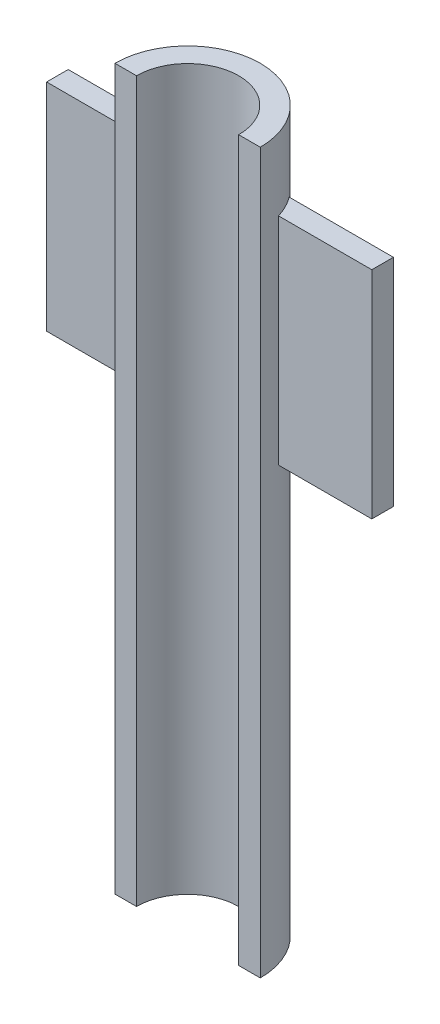
SolidWorks part; units mm, degrees
ref_plane "Front Plane" through (0, 0, 0) normal (0, 0, 1) x (1, 0, 0)
ref_plane "Top Plane" through (0, 0, 0) normal (0, 1, 0) x (1, 0, 0)
ref_plane "Right Plane" through (0, 0, 0) normal (1, 0, 0) x (0, 0, -1)
sketch "Sketch1" plane through (0, 0, 0) normal (0, 1, 0) x (1, 0, 0)
  circle A0 centre (0, 0) radius 7.1
  circle A1 centre (0, 0) radius 10.1
  dimension "D1" = 3
  dimension "D2" = 14.2
extrude "Boss-Extrude1" add sketch "Sketch1" along normal mid plane 100
sketch "Sketch2" plane through (0, -50, 0) normal (0, -1, 0) x (1, 0, 0)
  circle A0 centre (0, 0) radius 11.1
sketch "Sketch3" plane through (0, 0, 0) normal (0, 0, 1) x (1, 0, 0)
  line L1 (-101.5851, -102.8012) -> (101.5851, -102.8012)
  line L2 (-101.5851, -102.8012) -> (-101.5851, 102.8012)
  line L3 (-101.5851, 102.8012) -> (101.5851, 102.8012)
  line L4 (101.5851, -102.8012) -> (101.5851, 102.8012)
  line L5 (-101.5851, -102.8012) -> (101.5851, 102.8012) construction
  line L6 (-101.5851, 102.8012) -> (101.5851, -102.8012) construction
  point P0 (0, 0)
extrude "Cut-Extrude1" cut sketch "Sketch3" along normal through all
sketch "Sketch4" plane through (0, -50, 0) normal (0, -1, 0) x (1, 0, 0)
  circle A0 centre (0, 0) radius 10.1
  dimension "D1" = 20.2
ref_plane "Plane2" through (0, 0, -4.5) normal (0, 0, 1) x (1, 0, 0)
sketch "Sketch6" plane through (0, 0, -4.5) normal (0, 0, 1) x (1, 0, 0)
  line L0 (0, 17.3633) -> (0, 69.1455) construction
  line L1 (10.1, 50) -> (7.1, 50) construction
  line L2 (7.6, 40) -> (22.6, 40)
  line L3 (7.6, 40) -> (7.6, 10)
  line L4 (7.6, 10) -> (22.6, 10)
  line L5 (22.6, 40) -> (22.6, 10)
  line L7 (-22.6, 40) -> (-22.6, 10)
  line L8 (-7.6, 10) -> (-22.6, 10)
  line L9 (-7.6, 40) -> (-7.6, 10)
  line L10 (-7.6, 40) -> (-22.6, 40)
  dimension "D1" = 10
  dimension "D2" = 30
  dimension "D3" = 7.6
  dimension "D4" = 15
extrude "Boss-Extrude4" add sketch "Sketch6" along normal mid plane 3
sketch "Sketch7" plane through (0, 0, -6) normal (0, 0, -1) x (-1, 0, 0)
  line L0 (15.3623, 40) -> (15.3623, 10) construction
  line L1 (8.1247, 40) -> (22.6, 40) construction
  line L2 (22.6, 10) -> (8.1247, 10) construction
  line L3 (0, 0) -> (0, 47.416) construction
  text T0 "A2N\r\n2mm mold" font "Century Gothic" height in points 11
extrude "Boss-Extrude5" add sketch "Sketch7" along normal blind 1.5
